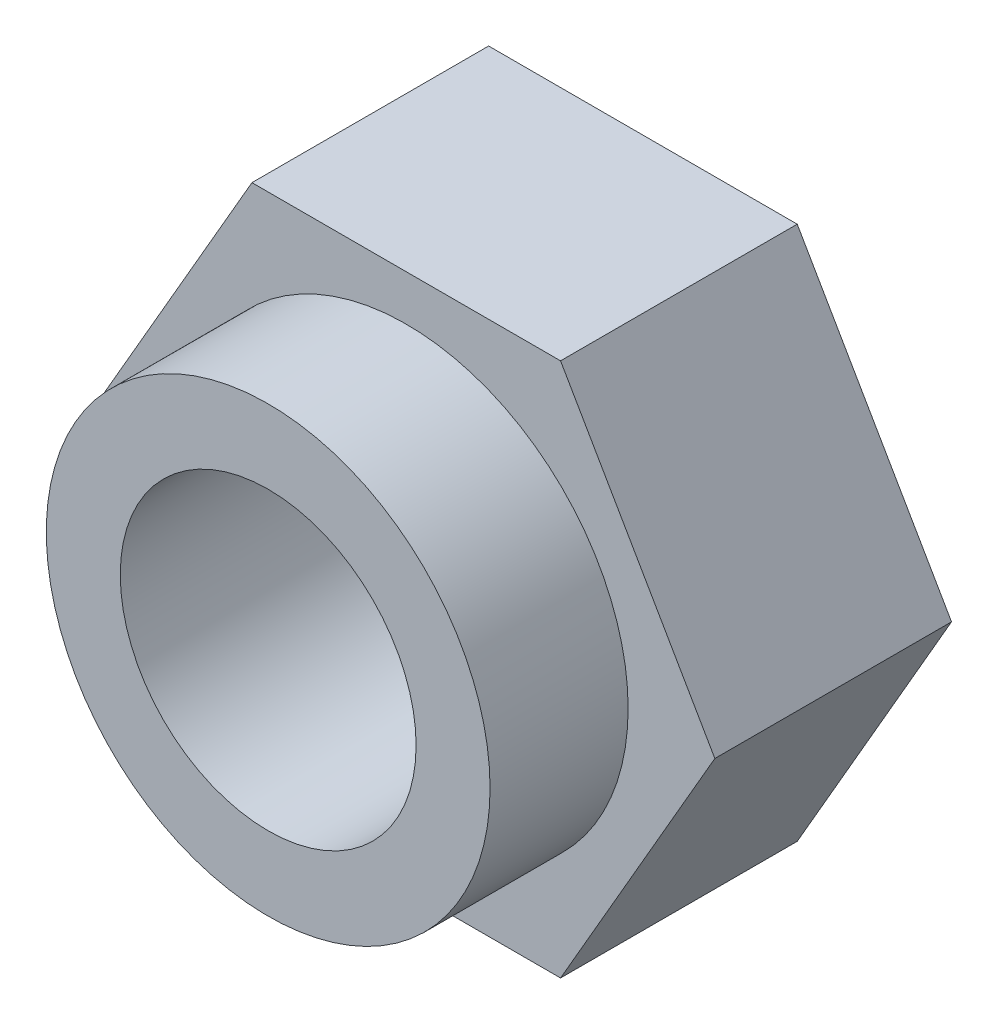
SolidWorks part; units mm, degrees
material "AISI 304"
ref_plane "前视基准面" through (0, 0, 0) normal (0, 0, 1) x (1, 0, 0)
ref_plane "上视基准面" through (0, 0, 0) normal (0, 1, 0) x (1, 0, 0)
ref_plane "右视基准面" through (0, 0, 0) normal (1, 0, 0) x (0, 0, -1)
sketch "草图1" plane through (0, 0, 0) normal (0, 0, 1) x (1, 0, 0)
  line L1 (3.1292, 0) -> (1.5646, 2.71)
  line L2 (1.5646, 2.71) -> (-1.5646, 2.71)
  line L3 (-1.5646, 2.71) -> (-3.1292, 0)
  line L4 (-3.1292, 0) -> (-1.5646, -2.71)
  line L5 (-1.5646, -2.71) -> (1.5646, -2.71)
  line L6 (1.5646, -2.71) -> (3.1292, 0)
  circle A0 centre (0, 0) radius 2.71 construction
  dimension "D1" = 5.42
extrude "凸台-拉伸1" add sketch "草图1" along normal blind 2.4
sketch "草图2" plane through (0, 0, 2.4) normal (0, 0, 1) x (1, 0, 0)
  circle A0 centre (0, 0) radius 2.25
  dimension "D1" = 4.5
extrude "凸台-拉伸2" add sketch "草图2" along normal blind 1.4
sketch "草图3" plane through (0, 0, 3.8) normal (0, 0, 1) x (1, 0, 0)
  circle A0 centre (0, 0) radius 1.5
  dimension "D1" = 3
extrude "切除-拉伸1" cut sketch "草图3" against normal blind 4.4
